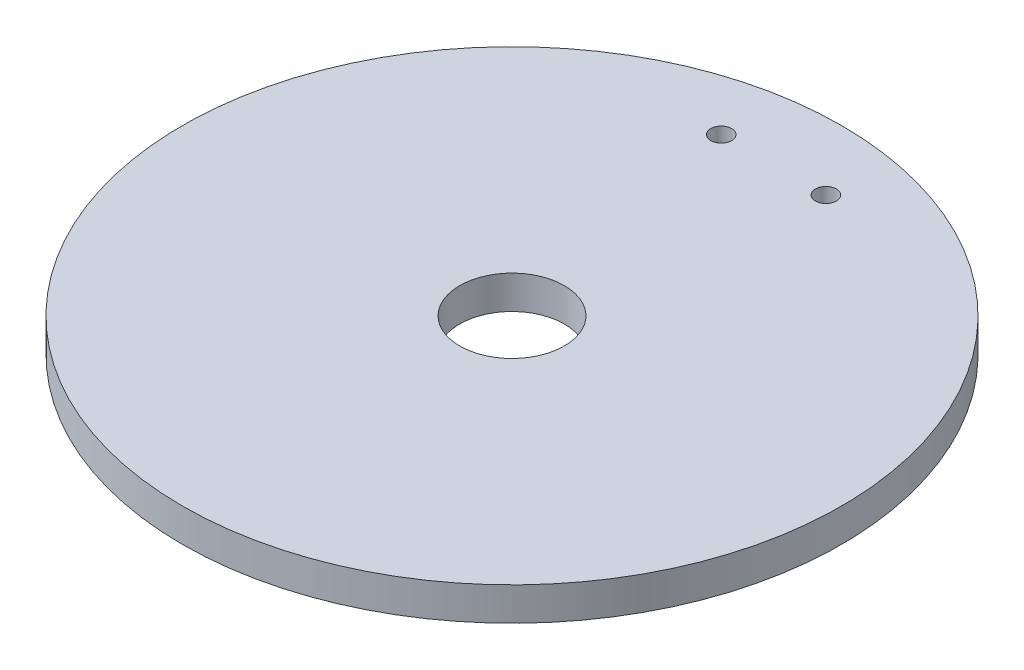
SolidWorks part; units mm, degrees
ref_plane "Front Plane" through (0, 0, 0) normal (0, 0, 1) x (1, 0, 0)
ref_plane "Top Plane" through (0, 0, 0) normal (0, 1, 0) x (1, 0, 0)
ref_plane "Right Plane" through (0, 0, 0) normal (1, 0, 0) x (0, 0, -1)
sketch "Sketch1" plane through (0, 0, 0) normal (0, 1, 0) x (1, 0, 0)
  circle A0 centre (0, 0) radius 31.5
  circle A1 centre (0, 0) radius 5
  dimension "D1" = 63
  dimension "D2" = 10
extrude "Boss-Extrude1" add sketch "Sketch1" along normal blind 3.18
sketch "Sketch2" plane through (0, 3.18, 0) normal (0, 1, 0) x (1, 0, 0)
  line L0 (0, 0) -> (0, 61.0259) construction
  circle A0 centre (0, 29) radius 1
  dimension "D1" = 29
  dimension "D2" = 2
extrude "Cut-Extrude1" [suppressed] cut sketch "Sketch2" against normal through all
pattern_circular "CirPattern1" [suppressed] count 2 every 20
mirror "Mirror1" [suppressed] about plane through (0, 0, 0) normal (0, 0, 1)
sketch "Sketch3" plane through (0, 3.18, 0) normal (0, 1, 0) x (1, 0, 0)
  line L0 (0, 0) -> (0, 47.1318) construction
  line L1 (0, 0) -> (41.784, 0) construction
  line L2 (-5, 25) -> (5, 25) construction
  circle A1 centre (-5, 25) radius 1
  circle A2 centre (5, 25) radius 1
  dimension "D1" = 2
  dimension "D2" = 10
  dimension "D3" = 25
extrude "Cut-Extrude2" cut sketch "Sketch3" against normal through all
